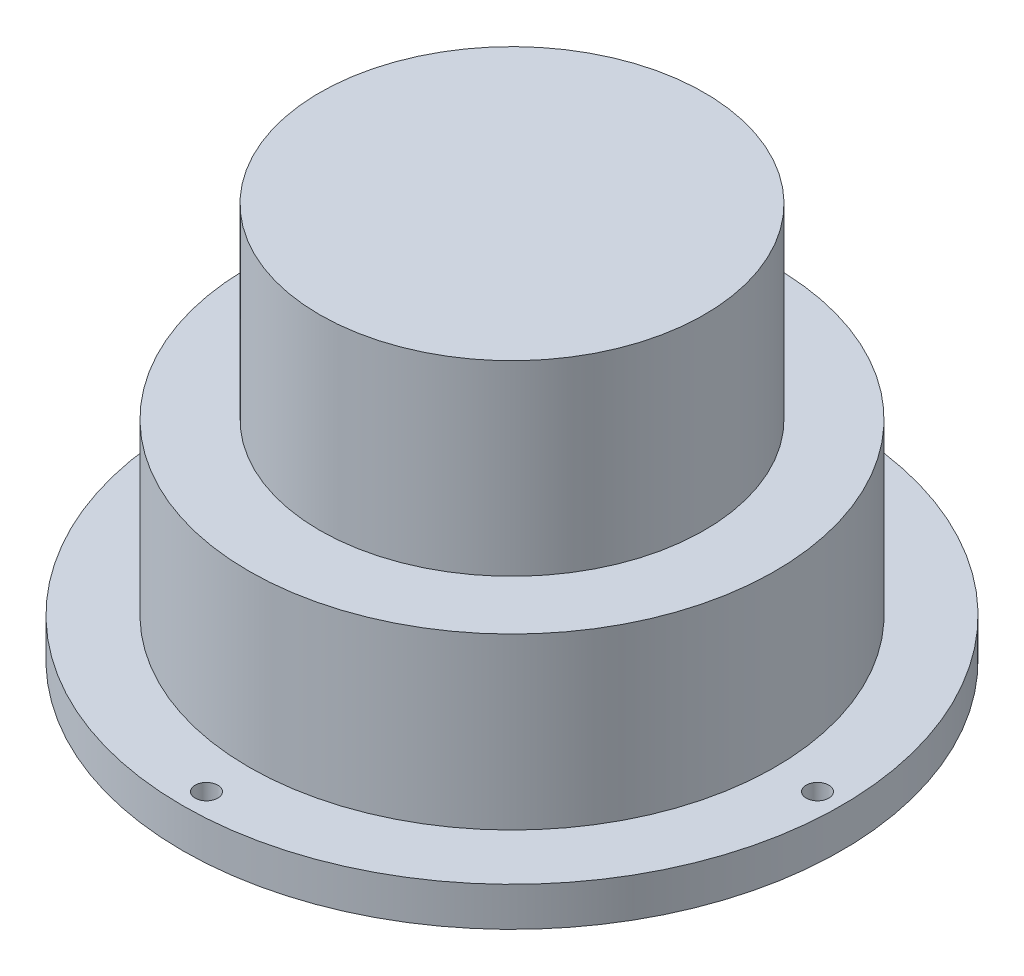
SolidWorks part; units mm, degrees
ref_plane "Front" through (0, 0, 0) normal (0, 0, 1) x (1, 0, 0)
ref_plane "Top" through (0, 0, 0) normal (0, 1, 0) x (1, 0, 0)
ref_plane "Right" through (0, 0, 0) normal (1, 0, 0) x (0, 0, -1)
sketch "Sketch1" plane through (0, 0, 0) normal (0, 1, 0) x (1, 0, 0)
  circle A0 centre (0, 0) radius 58.25
  dimension "D1" = 116.5
extrude "Boss-Extrude1" add sketch "Sketch1" along normal blind 6.9
sketch "Sketch2" plane through (0, 6.9, 0) normal (0, 1, 0) x (1, 0, 0)
  circle A0 centre (0, 0) radius 54
  circle A1 centre (0, 54) radius 2
  circle A2 centre (-54, 0) radius 2
  circle A3 centre (0, -54) radius 2
  circle A4 centre (54, 0) radius 2
  dimension "D1" = 108
  dimension "D2" = 4
  dimension "D3" = 4
  dimension "D4" = 4
  dimension "D5" = 4
extrude "Cut-Extrude1" cut sketch "Sketch2" against normal blind 6.9 contours A0 A2 | A0 A2 | A0 A1 | A0 A1 | A0 A4 | A0 A4 | A0 A3 | A0 A3
sketch "Sketch3" plane through (0, 6.9, 0) normal (0, 1, 0) x (1, 0, 0)
  circle A0 centre (0, 0) radius 46.5
  dimension "D1" = 93
extrude "Boss-Extrude2" add sketch "Sketch3" along normal blind 30
sketch "Sketch4" plane through (0, 36.9, 0) normal (0, 1, 0) x (1, 0, 0)
  circle A0 centre (0, 0) radius 34
  dimension "D1" = 68
extrude "Boss-Extrude3" add sketch "Sketch4" along normal blind 33
